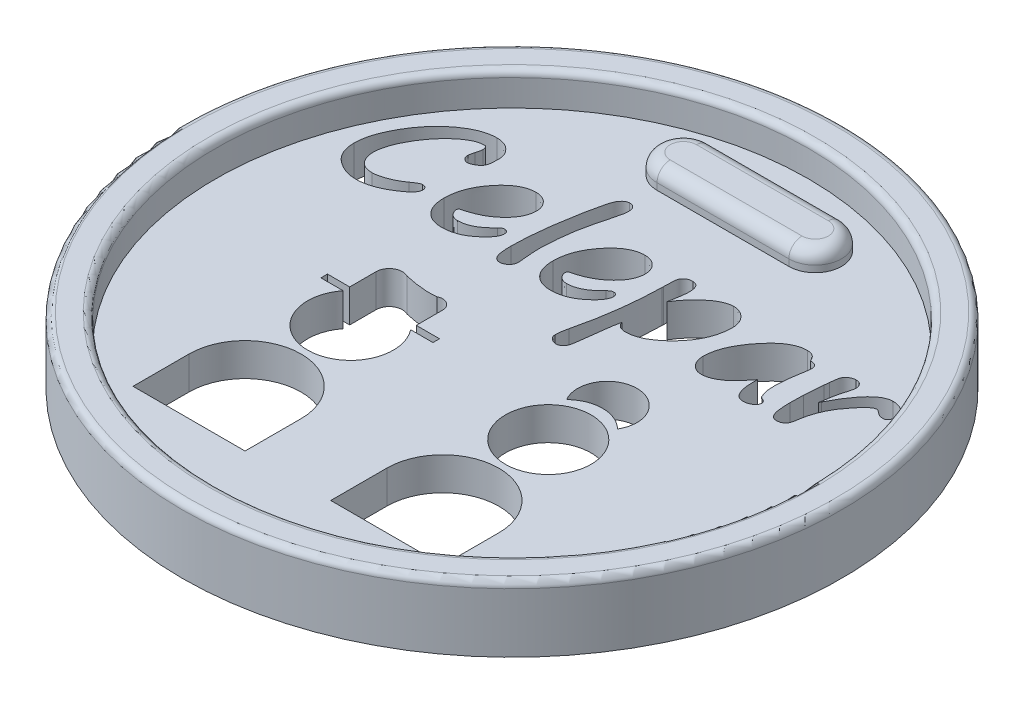
SolidWorks part; units mm, degrees
ref_plane "Front Plane" through (0, 0, 0) normal (0, 0, 1) x (1, 0, 0)
ref_plane "Top Plane" through (0, 0, 0) normal (0, 1, 0) x (1, 0, 0)
ref_plane "Right Plane" through (0, 0, 0) normal (1, 0, 0) x (0, 0, -1)
sketch "Sketch1" plane through (0, 0, 0) normal (0, 1, 0) x (1, 0, 0)
  circle A0 centre (0, 0) radius 50
  dimension "D1" = 100
extrude "Boss-Extrude1" add sketch "Sketch1" along normal blind 10 contours A0
sketch "Sketch2" plane through (0, 10, 0) normal (0, 1, 0) x (1, 0, 0)
  circle A0 centre (0, 0) radius 45
  dimension "D1" = 90
extrude "Cut-Extrude1" cut sketch "Sketch2" against normal blind 5
sketch "Sketch3" plane through (0, 5, 0) normal (0, 1, 0) x (1, 0, 0)
  text T0 "<b>Celepar</b>" font "Segoe Print" height 15
extrude "Cut-Extrude3" cut sketch "Sketch3" against normal blind 5
sketch "Sketch4" plane through (0, 5, 0) normal (0, 1, 0) x (1, 0, 0)
  line L2 (-24, -25) -> (-24, -33.5)
  line L3 (-24, -33.5) -> (-7, -33.5)
  line L4 (-7, -25) -> (-7, -33.5)
  line L6 (6, -25) -> (6, -33.5)
  line L7 (6, -33.5) -> (23, -33.5)
  line L8 (23, -25) -> (23, -33.5)
  circle A0 centre (14.5, -9) radius 6.5
  circle A1 centre (-15.5, -9) radius 6.5
  arc A2 (18.3615, -2.3501) -> (10.6385, -2.3501) centre (14.5, -0.0395) ccw
  arc A3 (18.3615, -2.3501) -> (10.6385, -2.3501) centre (14.5, -6.2666) ccw
  arc A4 (-7, -25) -> (-24, -25) centre (-15.5, -25) ccw
  arc A5 (23, -25) -> (6, -25) centre (14.5, -25) ccw
  circle A6 centre (0, 0) radius 45 construction
  dimension "D2" = 17
  dimension "D5" = 8.5
  dimension "D6" = 13
  dimension "D7" = 13
  dimension "D8" = 9
  dimension "D9" = 30
  dimension "D10" = 30
  dimension "D11" = 30
  dimension "D12" = 30
  dimension "D13" = 17
  dimension "D16" = 25
  dimension "D17" = 25
  dimension "D19" = 16
  dimension "D20" = 16
  dimension "D21" = 8.5
  dimension "D24" = 0
  dimension "D25" = 11
  dimension "D1" = 17
  dimension "D18" = 6
extrude "Cut-Extrude4" cut sketch "Sketch4" against normal blind 5
sketch "Sketch5" plane through (0, 5, 0) normal (0, 1, 0) x (1, 0, 0)
  line L0 (-10.5235, -4) -> (-7, -4)
  line L1 (-24, -4) -> (-20.6235, -4)
  line L2 (-24, -4) -> (-24, -5)
  line L3 (-24, -5) -> (-7, -5)
  line L4 (-7, -4) -> (-7, -5)
  line L5 (-20.6235, -5) -> (-10.5235, -5)
  line L6 (-20.6235, -4) -> (-20.6235, 0)
  line L8 (-10.5235, -4) -> (-10.5235, 0)
  circle A0 centre (-15.5, -9) radius 6.5 construction
  arc A1 (-17.6954, 1.7716) -> (-20.6235, 0) centre (-18.6235, 0) ccw
  arc A2 (-10.5235, 0) -> (-12.6988, 1.3394) centre (-12.0235, 0) ccw
  spline S0 degree 3 poles (-17.6954, 1.7716) (-16.8826, 1.5861) (-15.8366, 1.3941) (-14.1176, 1.238) (-13.2832, 1.2468) (-12.6988, 1.3394) knots 0.139431 0.139431 0.139431 0.139431 0.494248 0.567662 0.873573 0.873573 0.873573 0.873573
  point P16 (-14.9012, 1.3099)
  point P18 (0, 0)
  point P19 (0, 0)
  dimension "D5" = 4
  dimension "D6" = 3
  dimension "D1" = 17
  dimension "D2" = 8.5
  dimension "D3" = 5
  dimension "D4" = 1
  dimension "D7" = 10.1
extrude "Cut-Extrude5" cut sketch "Sketch5" against normal blind 5 contours S0 A1 L6 L1 L2 L3 L4 L0 L8 A2
sketch "Sketch6" plane through (0, 5, 0) normal (0, 1, 0) x (1, 0, 0)
  line L0 (-10, 36) -> (10, 36) construction
  line L1 (-10, 40) -> (10, 40)
  line L2 (-10, 32) -> (10, 32)
  arc A0 (-10, 40) -> (-10, 32) centre (-10, 36) ccw
  arc A1 (10, 32) -> (10, 40) centre (10, 36) ccw
  point P2 (0, 36)
  dimension "D3" = 4
  dimension "D4" = 20
  dimension "D1" = 0
  dimension "D2" = 36
extrude "Boss-Extrude2" add sketch "Sketch6" along normal blind 3
sketch "Sketch8" plane through (0, 5, 0) normal (0, 1, 0) x (1, 0, 0)
  arc A0 (21.9203, 16.4407) -> (19.1823, 18.2468) centre (21.343, 18.544) ccw
  arc A1 (19.1823, 18.2468) -> (21.9203, 16.4407) centre (19.4005, 15.5992) ccw
extrude "Cut-Extrude9" cut sketch "Sketch8" against normal blind 5
sketch "Sketch9" plane through (0, 5, 0) normal (0, 1, 0) x (1, 0, 0)
  arc A0 (-19.2783, 17.9474) -> (-20.9965, 19.7204) centre (-19.5173, 19.4349) ccw
  arc A1 (-20.9965, 19.7204) -> (-19.2783, 17.9474) centre (-21.3139, 17.6938) ccw
  arc A2 (-2.8383, 17.687) -> (-4.8066, 19.6553) centre (-3.0587, 19.4349) ccw
  arc A3 (-4.8066, 19.6553) -> (-2.8383, 17.687) centre (-4.8205, 17.6732) ccw
  arc A4 (10.3962, 15.8898) -> (7.0452, 18.1827) centre (9.7185, 18.4945) ccw
  arc A5 (7.0452, 18.1827) -> (10.3962, 15.8898) centre (7.3761, 15.071) ccw
  point P1 (0, 0)
extrude "Cut-Extrude10" cut sketch "Sketch9" against normal blind 5 contours A1 A0 | A3 A2 | A5 A4
fillet "Fillet3" radius 1 2 edges at (0, 10, 45) (0, 10, 50)
fillet "Fillet4" radius 2 4 edges at (-14, 8, -36) (0, 8, -40) (14, 8, -36) (0, 8, -32)
